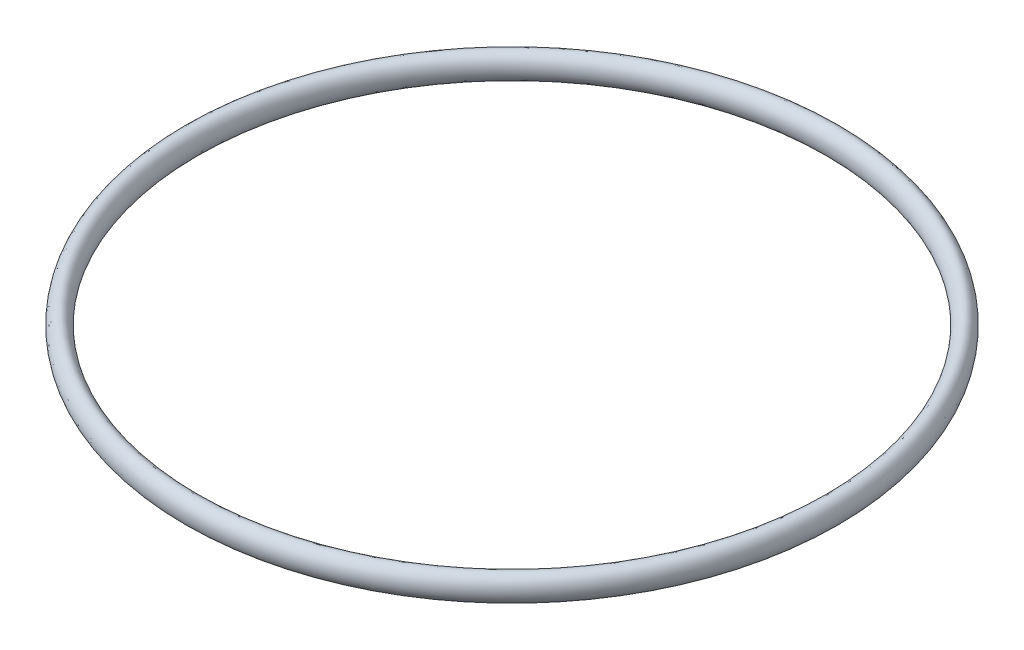
SolidWorks part; units mm, degrees
ref_plane "Front Plane" through (0, 0, 0) normal (0, 0, 1) x (1, 0, 0)
ref_plane "Top Plane" through (0, 0, 0) normal (0, 1, 0) x (1, 0, 0)
ref_plane "Right Plane" through (0, 0, 0) normal (1, 0, 0) x (0, 0, -1)
sketch "Sketch1" plane through (0, 0, 0) normal (1, 0, 0) x (0, 0, -1)
  line L0 (0, 0) -> (49.25, 0) construction
  line L1 (0, 4.5155) -> (0, 0) construction
  ellipse E0 centre (49.25, 0) end of major axis (49.25, -2) minor radius 1.5
  point P4 (0, 0)
  dimension "D1" = 4
  dimension "D2" = 3
  dimension "D3" = 49.25
revolve "Revolve1" add sketch "Sketch1" angle 360 about L1
